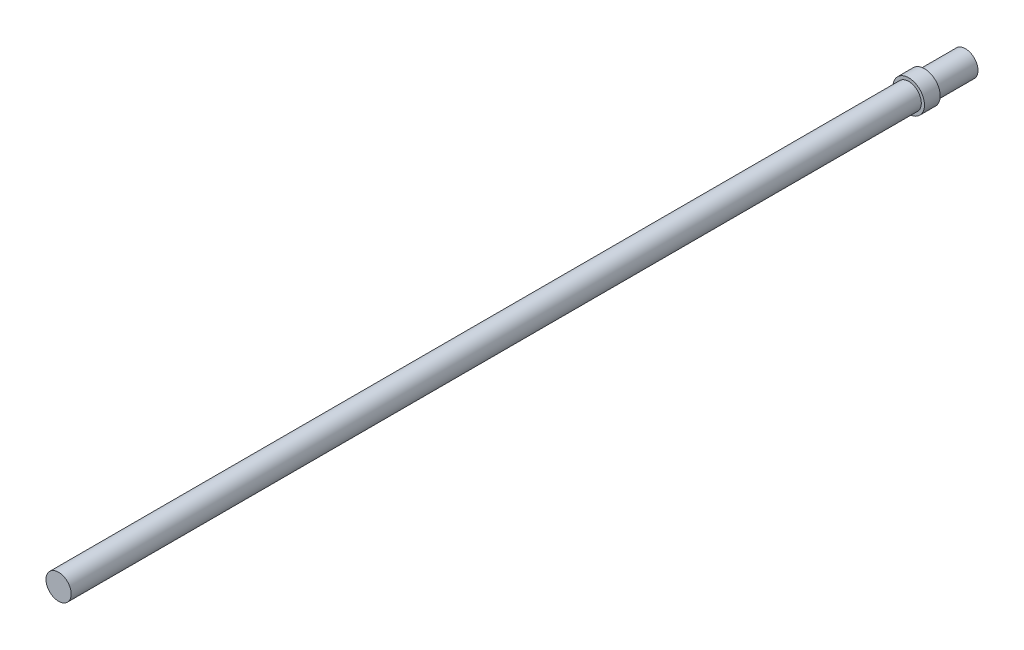
SolidWorks part; units mm, degrees
ref_plane "Front Plane" through (0, 0, 0) normal (0, 0, 1) x (1, 0, 0)
ref_plane "Top Plane" through (0, 0, 0) normal (0, 1, 0) x (1, 0, 0)
ref_plane "Right Plane" through (0, 0, 0) normal (1, 0, 0) x (0, 0, -1)
sketch "Sketch1" plane through (0, 0, 0) normal (0, 0, 1) x (1, 0, 0)
  circle A0 centre (0, 0) radius 4
extrude "Boss-Extrude1" add sketch "Sketch1" along normal blind 270
sketch "Sketch2" plane through (0, 0, 0) normal (0, 0, 1) x (1, 0, 0)
  circle A0 centre (0, 0) radius 5
extrude "Boss-Extrude2" add sketch "Sketch2" against normal blind 5
sketch "Sketch3" plane through (0, 0, 0) normal (0, 0, 1) x (1, 0, 0)
  circle A0 centre (0, 0) radius 4
extrude "Boss-Extrude3" add sketch "Sketch3" against normal blind 18
